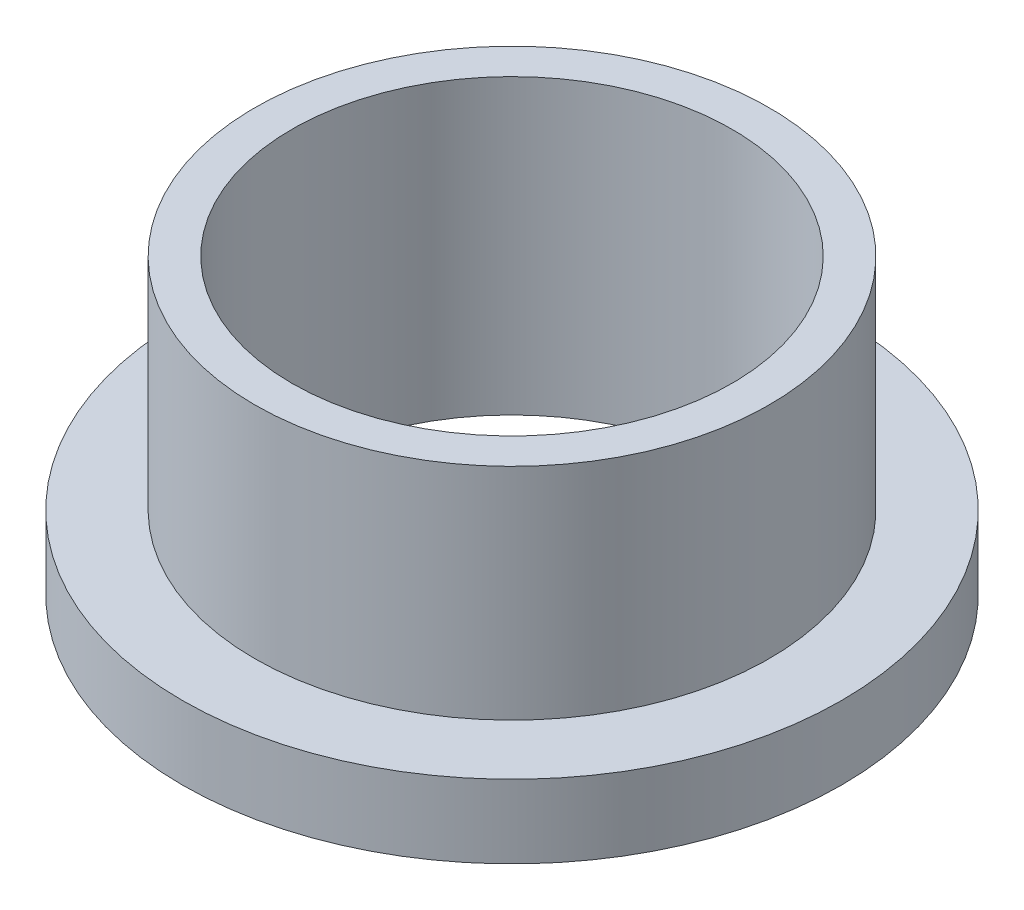
SolidWorks part; units mm, degrees
ref_plane "Front" through (0, 0, 0) normal (0, 0, 1) x (1, 0, 0)
ref_plane "Top" through (0, 0, 0) normal (0, 1, 0) x (1, 0, 0)
ref_plane "Right" through (0, 0, 0) normal (1, 0, 0) x (0, 0, -1)
sketch "Sketch1" plane through (0, 0, 0) normal (0, 1, 0) x (1, 0, 0)
  circle A0 centre (0, 0) radius 9.5377
  circle A1 centre (0, 0) radius 11.1506
  circle A2 centre (0, 0) radius 14.2875
  dimension "ID" = 19.0754
  dimension "OD" = 22.3012
  dimension "FlangeOD" = 28.575
sketch "Sketch2" plane through (0, 0, 0) normal (0, 1, 0) x (1, 0, 0)
  circle A0 centre (0, 0) radius 9.5377 construction
  circle A1 centre (0, 0) radius 11.1506 construction
  circle A2 centre (0, 0) radius 9.5377
  circle A3 centre (0, 0) radius 11.1506
extrude "Boss-Extrude1" add sketch "Sketch2" along normal blind 12.7
sketch "Sketch3" plane through (0, 0, 0) normal (0, 1, 0) x (1, 0, 0)
  circle A0 centre (0, 0) radius 14.2875 construction
  circle A1 centre (0, 0) radius 11.1506 construction
  circle A2 centre (0, 0) radius 14.2875
  circle A3 centre (0, 0) radius 11.1506
extrude "Boss-Extrude2" add sketch "Sketch3" along normal blind 3.175
